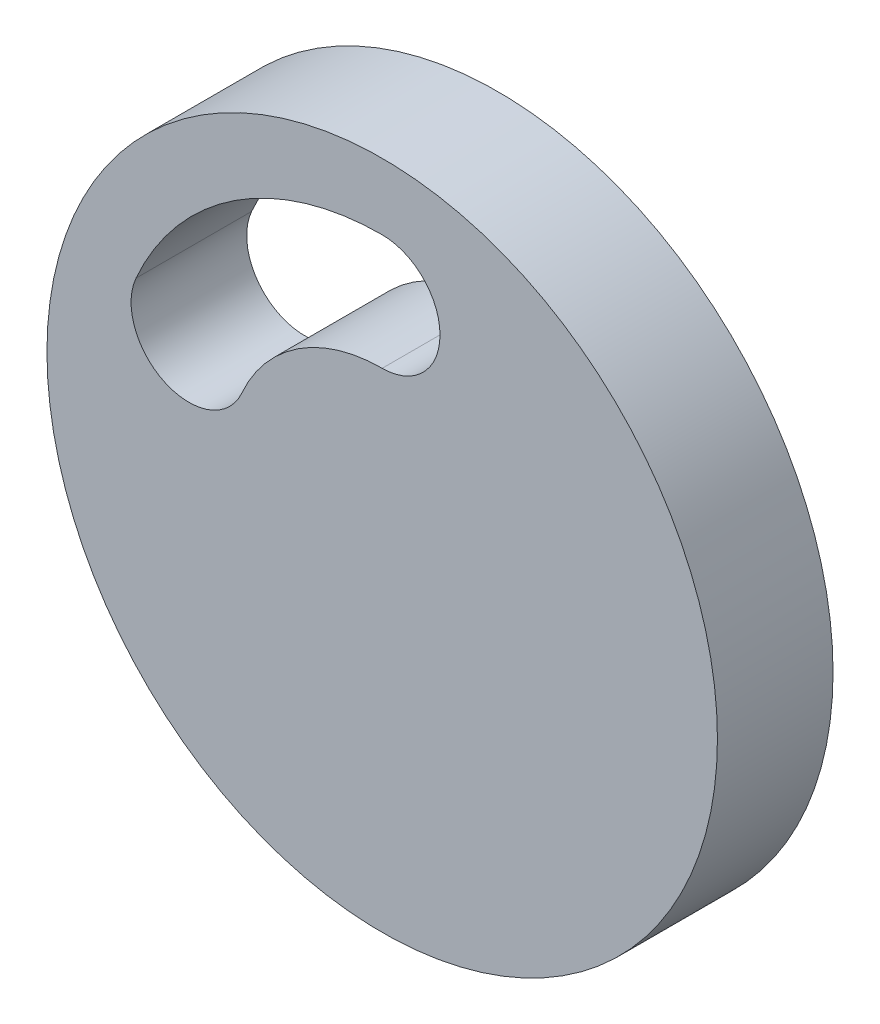
SolidWorks part; units mm, degrees
ref_plane "前基準面" through (0, 0, 0) normal (0, 0, 1) x (1, 0, 0)
ref_plane "上基準面" through (0, 0, 0) normal (0, 1, 0) x (1, 0, 0)
ref_plane "右基準面" through (0, 0, 0) normal (1, 0, 0) x (0, 0, -1)
sketch "草圖1" plane through (0, 0, 0) normal (0, 0, 1) x (1, 0, 0)
  circle A0 centre (0, 0) radius 2.8999
  arc A1 (-1.6721, 0.7354) -> (0, 1.8266) centre (0, 0) cw construction
  arc A2 (0, 2.3266) -> (-2.1298, 0.9366) centre (0, 0) ccw
  arc A3 (0, 1.3266) -> (-1.2144, 0.5341) centre (0, 0) ccw
  arc A4 (0, 1.3266) -> (0, 2.3266) centre (0, 1.8266) ccw
  arc A5 (-2.1298, 0.9366) -> (-1.2144, 0.5341) centre (-1.6721, 0.7354) ccw
  point P5 (-0.9983, 1.5297)
  dimension "D1" = 0.5
extrude "填料-伸長1" add sketch "草圖1" along normal blind 1
